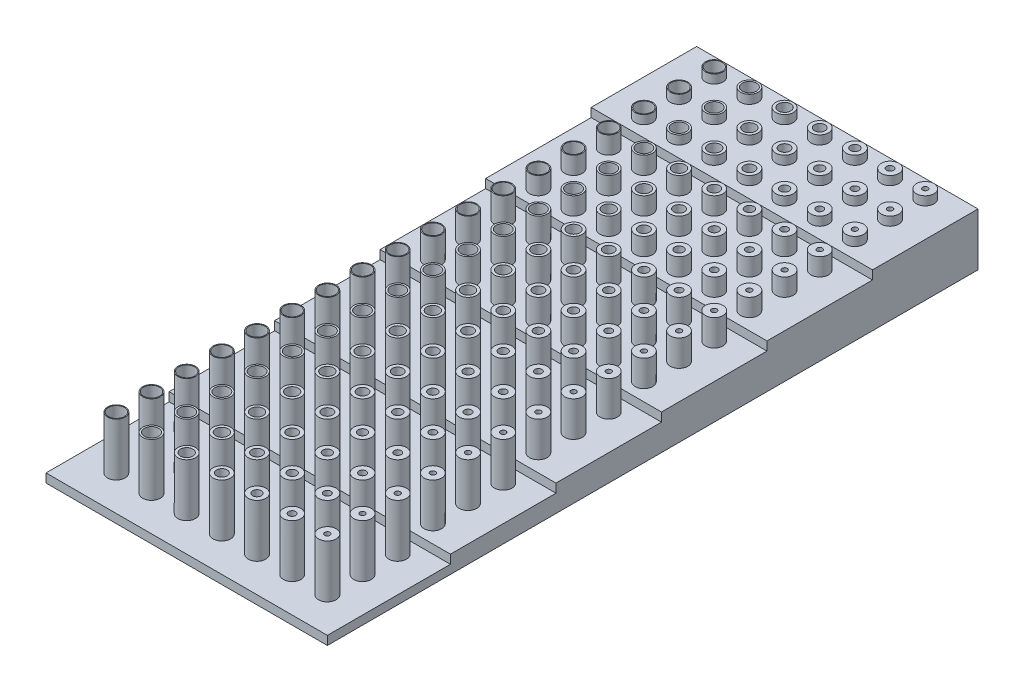
SolidWorks part; units mm, degrees
ref_plane "Front Plane" through (0, 0, 0) normal (0, 0, 1) x (1, 0, 0)
ref_plane "Top Plane" through (0, 0, 0) normal (0, 1, 0) x (1, 0, 0)
ref_plane "Right Plane" through (0, 0, 0) normal (1, 0, 0) x (0, 0, -1)
sketch "Sketch1" plane through (0, 0, 0) normal (0, 1, 0) x (1, 0, 0)
  line L1 (0, 0) -> (16, 0)
  line L2 (0, 0) -> (0, 37)
  line L3 (0, 37) -> (16, 37)
  line L4 (16, 0) -> (16, 37)
  line L5 (0, 0) -> (16, 37) construction
  line L6 (0, 37) -> (16, 0) construction
  point P4 (8, 18.5)
  dimension "D1" = 16
  dimension "D2" = 37
extrude "Boss-Extrude1" add sketch "Sketch1" along normal blind 0.5
sketch "Sketch3" plane through (0, 0, 0) normal (0, 1, 0) x (1, 0, 0)
  line L0 (-0.55, 0) -> (0.55, 0) construction
  line L1 (0, -0.55) -> (0, 0.55) construction
  circle A0 centre (2, 2) radius 0.5
  dimension "D1" = 1
  dimension "D2" = 2
  dimension "D3" = 2
extrude "Extrude-Thin1" add sketch "Sketch3" along normal blind 3.5 thin thin type one direction reverse wall 0.05
sketch "Sketch4" plane through (0, 0.5, 0) normal (0, 1, 0) x (1, 0, 0)
  line L0 (2, 2) -> (16, 2) construction
  line L1 (16, 0) -> (16, 37) construction
  circle A0 centre (4, 2) radius 0.5
  circle A1 centre (2, 2) radius 0.45 construction
  point P9 (4, 2)
  point P10 (4, 2)
  dimension "D1" = 2
  dimension "D2" = 1
extrude "Extrude-Thin2" add sketch "Sketch4" along normal blind 3 thin thin type one direction reverse wall 0.1
sketch "Sketch5" plane through (0, 0.5, 0) normal (0, 1, 0) x (1, 0, 0)
  line L0 (6, 2) -> (4, 2) construction
  circle A0 centre (6, 2) radius 0.5
  point P2 (6, 2.1372)
  dimension "D2" = 1
  dimension "D1" = 2
extrude "Extrude-Thin3" add sketch "Sketch5" along normal blind 3 thin thin type one direction reverse wall 0.15
sketch "Sketch6" plane through (0, 0.5, 0) normal (0, 1, 0) x (1, 0, 0)
  line L0 (8, 2) -> (6, 2) construction
  circle A0 centre (8, 2) radius 0.5
  circle A1 centre (6, 2) radius 0.35 construction
  dimension "D2" = 1
  dimension "D1" = 2
extrude "Extrude-Thin4" add sketch "Sketch6" along normal blind 3 thin thin type one direction reverse wall 0.2
sketch "Sketch7" plane through (0, 0.5, 0) normal (0, 1, 0) x (1, 0, 0)
  line L0 (8, 2) -> (10, 2) construction
  circle A0 centre (10, 2) radius 0.5
  dimension "D1" = 1
  dimension "D2" = 2
extrude "Extrude-Thin5" add sketch "Sketch7" along normal blind 3 thin thin type one direction reverse wall 0.25
sketch "Sketch8" plane through (0, 0.5, 0) normal (0, 1, 0) x (1, 0, 0)
  line L0 (10, 2) -> (12, 2) construction
  circle A0 centre (12, 2) radius 0.5
  dimension "D1" = 1
  dimension "D2" = 2
extrude "Extrude-Thin6" add sketch "Sketch8" along normal blind 3 thin thin type one direction reverse wall 0.3
sketch "Sketch9" plane through (0, 0.5, 0) normal (0, 1, 0) x (1, 0, 0)
  line L0 (12, 2) -> (14, 2) construction
  circle A0 centre (14, 2) radius 0.5
  dimension "D1" = 1
  dimension "D2" = 2
extrude "Extrude-Thin7" add sketch "Sketch9" along normal blind 3 thin thin type one direction reverse wall 0.35
sketch "Sketch12" plane through (0, 0.5, 0) normal (0, 1, 0) x (1, 0, 0)
  circle A0 centre (14, 2) radius 0.15 construction
  circle A1 centre (12, 2) radius 0.2 construction
  circle A2 centre (10, 2) radius 0.25 construction
  circle A3 centre (8, 2) radius 0.3 construction
  circle A4 centre (6, 2) radius 0.35 construction
  circle A5 centre (4, 2) radius 0.4 construction
  circle A6 centre (2, 2) radius 0.45 construction
  circle A7 centre (14, 2) radius 0.15
  circle A8 centre (12, 2) radius 0.2
  circle A9 centre (10, 2) radius 0.25
  circle A10 centre (8, 2) radius 0.3
  circle A11 centre (6, 2) radius 0.35
  circle A12 centre (4, 2) radius 0.4
  circle A13 centre (2, 2) radius 0.45
extrude "Cut-Extrude1" cut sketch "Sketch12" against normal through all both and the other way through all
sketch "Sketch10" plane through (0, 0, 0) normal (-1, 0, 0) x (0, 0, 1)
  line L0 (-7, 0.5) -> (-7, 1)
  line L1 (-37, 0.5) -> (0, 0.5) construction
  line L2 (-7, 1) -> (-13, 1)
  line L3 (-13, 1) -> (-13, 1.5)
  line L4 (-13, 1.5) -> (-19, 1.5)
  line L5 (-19, 1.5) -> (-19, 2)
  line L6 (-19, 2) -> (-25, 2)
  line L7 (-25, 2) -> (-25, 2.5)
  line L8 (-25, 2.5) -> (-31, 2.5)
  line L9 (0, -1.925) -> (0, 1.925) construction
  line L10 (-31, 2.5) -> (-31, 3)
  line L11 (-31, 3) -> (-37, 3)
  line L12 (-37, 3) -> (-37, 0.5)
  line L13 (-37, 0.5) -> (-7, 0.5)
  dimension "D1" = 0.5
  dimension "D2" = 6
  dimension "D3" = 7
extrude "Boss-Extrude2" add sketch "Sketch10" against normal up to surface (16 mm away) up to face at (16, 0.25, -18.5)
pattern_linear "LPattern1" count 18 spacing 2 along (0, 0, -1) of "Extrude-Thin2", "Extrude-Thin3", "Extrude-Thin4", "Extrude-Thin5", "Extrude-Thin6", "Extrude-Thin7", "Extrude-Thin1", "Cut-Extrude1"
